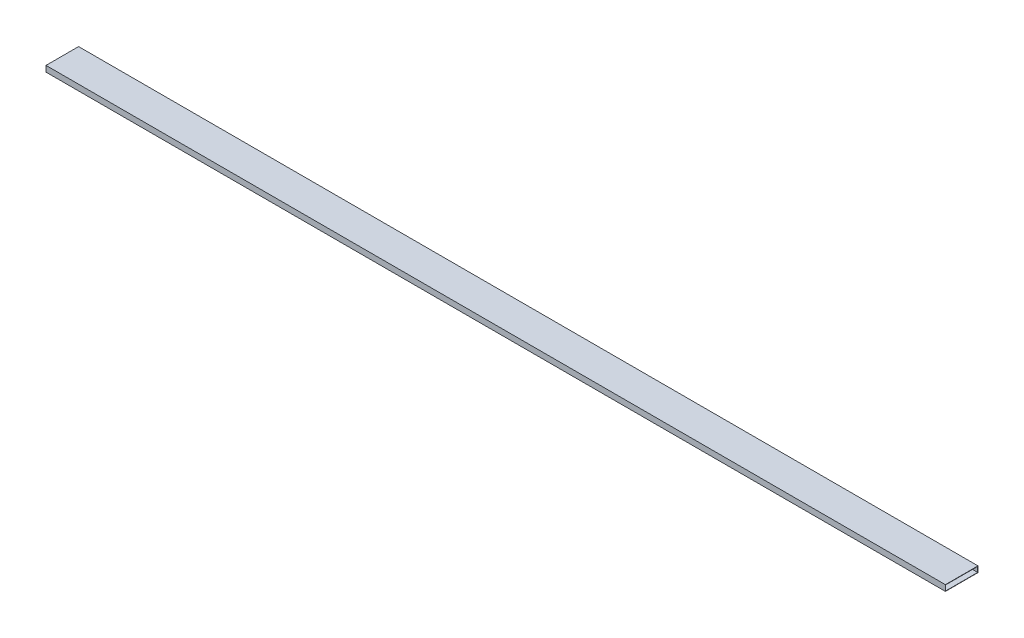
SolidWorks part; units mm, degrees
material "Carbon/Epoxy"
ref_plane "Front Plane" through (0, 0, 0) normal (0, 0, 1) x (1, 0, 0)
ref_plane "Top Plane" through (0, 0, 0) normal (0, 1, 0) x (1, 0, 0)
ref_plane "Right Plane" through (0, 0, 0) normal (1, 0, 0) x (0, 0, -1)
sketch "Sketch2" plane through (0, 0, 0) normal (1, 0, 0) x (0, 0, -1)
  line L15 (0.6096, -5.715) -> (0.6096, 5.715)
  line L16 (-62.8904, -5.715) -> (0.6096, -5.715)
  line L17 (-62.8904, 5.715) -> (-62.8904, -5.715)
  line L18 (0.6096, 5.715) -> (-62.8904, 5.715)
  line L19 (0.6096, -5.715) -> (0.6096, 5.715)
  line L20 (-62.8904, -5.715) -> (0.6096, -5.715)
  line L21 (-62.8904, 5.715) -> (-62.8904, -5.715)
  line L22 (0.6096, 5.715) -> (-62.8904, 5.715)
  line L23 (-62.2808, -5.1054) -> (0, -5.1054)
  line L24 (0, -5.1054) -> (0, 5.1054)
  line L25 (0, 5.1054) -> (-62.2808, 5.1054)
  line L26 (-62.2808, 5.1054) -> (-62.2808, -5.1054)
  line L27 (-62.2808, -5.1054) -> (0, -5.1054)
  line L28 (0, -5.1054) -> (0, 5.1054)
  line L29 (0, 5.1054) -> (-62.2808, 5.1054)
  line L30 (-62.2808, 5.1054) -> (-62.2808, -5.1054)
  dimension "D1" = 0.6096
  dimension "D2" = 0
extrude "Boss-Extrude1" add sketch "Sketch2" against normal up to vertex (1752.6 mm away)
equation "\"D1@Sketch2\"=3*0.008"
